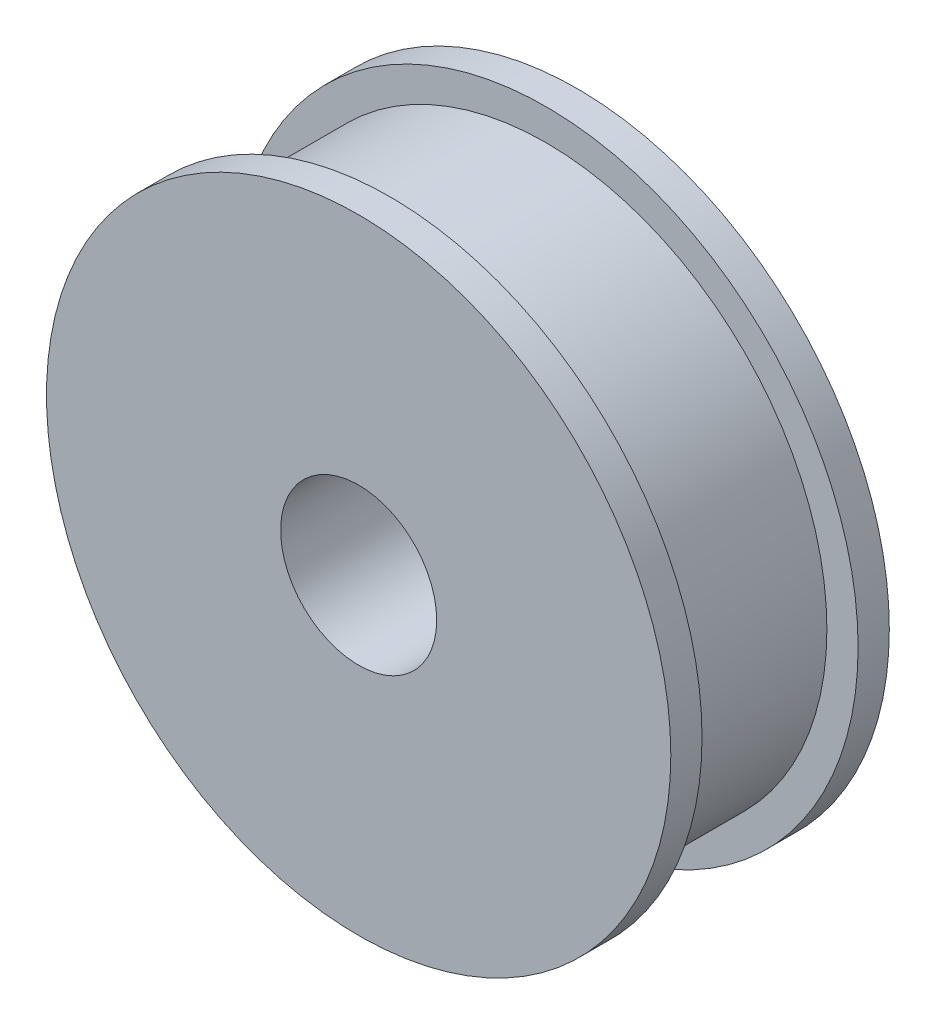
SolidWorks part; units mm, degrees
ref_plane "正面" through (0, 0, 0) normal (0, 0, 1) x (1, 0, 0)
ref_plane "平面" through (0, 0, 0) normal (0, 1, 0) x (1, 0, 0)
ref_plane "右側面" through (0, 0, 0) normal (1, 0, 0) x (0, 0, -1)
sketch "ｽｹｯﾁ2" plane through (0, 0, 0) normal (0, 0, 1) x (1, 0, 0)
  circle A0 centre (0, 0) radius 20
  dimension "D1" = 40
extrude "ﾎﾞｽ - 押し出し1" add sketch "ｽｹｯﾁ2" along normal blind 2
sketch "ｽｹｯﾁ3" plane through (0, 0, 2) normal (0, 0, 1) x (1, 0, 0)
  circle A0 centre (0, 0) radius 18
  dimension "D1" = 36
extrude "ﾎﾞｽ - 押し出し2" add sketch "ｽｹｯﾁ3" along normal blind 10
sketch "ｽｹｯﾁ4" plane through (0, 0, 12) normal (0, 0, 1) x (1, 0, 0)
  circle A0 centre (0, 0) radius 20 construction
  circle A1 centre (0, 0) radius 20
extrude "ﾎﾞｽ - 押し出し3" add sketch "ｽｹｯﾁ4" along normal blind 2
sketch "ｽｹｯﾁ5" plane through (0, 0, 14) normal (0, 0, 1) x (1, 0, 0)
  circle A0 centre (0, 0) radius 5
  dimension "D1" = 10
extrude "ｶｯﾄ - 押し出し1" cut sketch "ｽｹｯﾁ5" against normal through all
